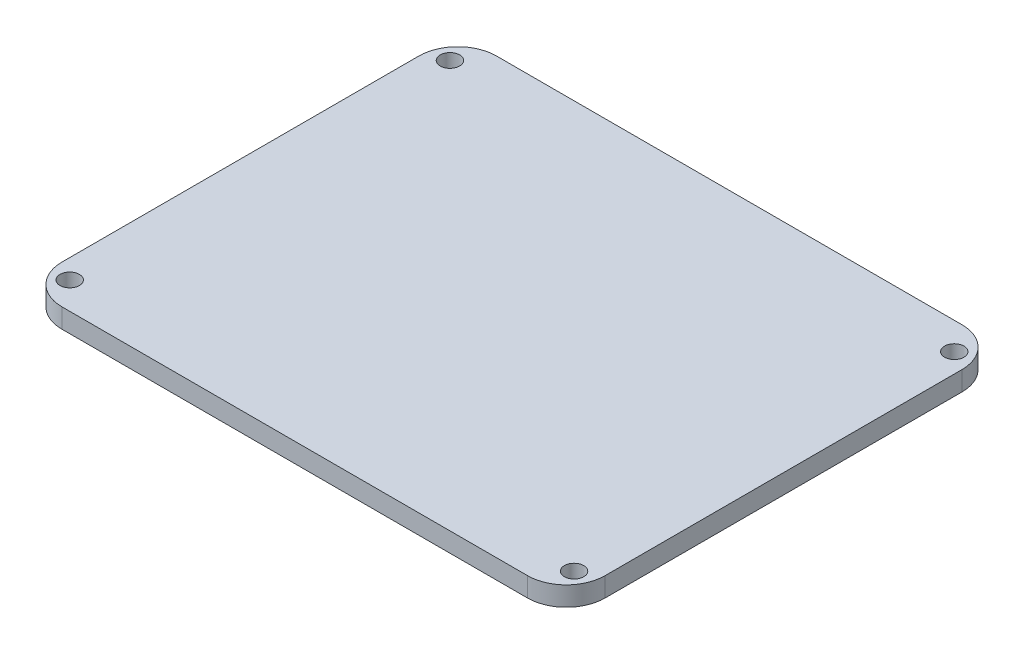
SolidWorks part; units mm, degrees
ref_plane "Front Plane" through (0, 0, 0) normal (0, 0, 1) x (1, 0, 0)
ref_plane "Top Plane" through (0, 0, 0) normal (0, 1, 0) x (1, 0, 0)
ref_plane "Right Plane" through (0, 0, 0) normal (1, 0, 0) x (0, 0, -1)
sketch "Sketch1" plane through (0, 0, 0) normal (0, 1, 0) x (1, 0, 0)
  line L0 (-30, 28) -> (30, 28)
  line L5 (-35, 23) -> (-35, -23)
  line L6 (-30, -28) -> (30, -28)
  line L7 (35, 23) -> (35, -23)
  arc A0 (-30, 28) -> (-35, 23) centre (-30, 23) ccw
  arc A1 (35, 23) -> (30, 28) centre (30, 23) ccw
  arc A2 (-35, -23) -> (-30, -28) centre (-30, -23) ccw
  arc A3 (35, -23) -> (30, -28) centre (30, -23) cw
  circle A4 centre (-32.5, 24.5) radius 1.25
  circle A5 centre (32.5, 24.5) radius 1.25
  circle A6 centre (32.5, -24.5) radius 1.25
  circle A7 centre (-32.5, -24.5) radius 1.25
  point P20 (0, 28)
  point P22 (35, 0)
  dimension "D3" = 5
  dimension "D6" = 2.5
  dimension "D7" = 3.5
  dimension "D8" = 3.5
  dimension "D9" = 2.5
  dimension "D10" = 2.5
  dimension "D11" = 3.5
  dimension "D12" = 2.5
  dimension "D1" = 60
  dimension "D2" = 46
  dimension "D4" = 3.5
  dimension "D5" = 2.5
extrude "Boss-Extrude1" add sketch "Sketch1" along normal blind 2.5
